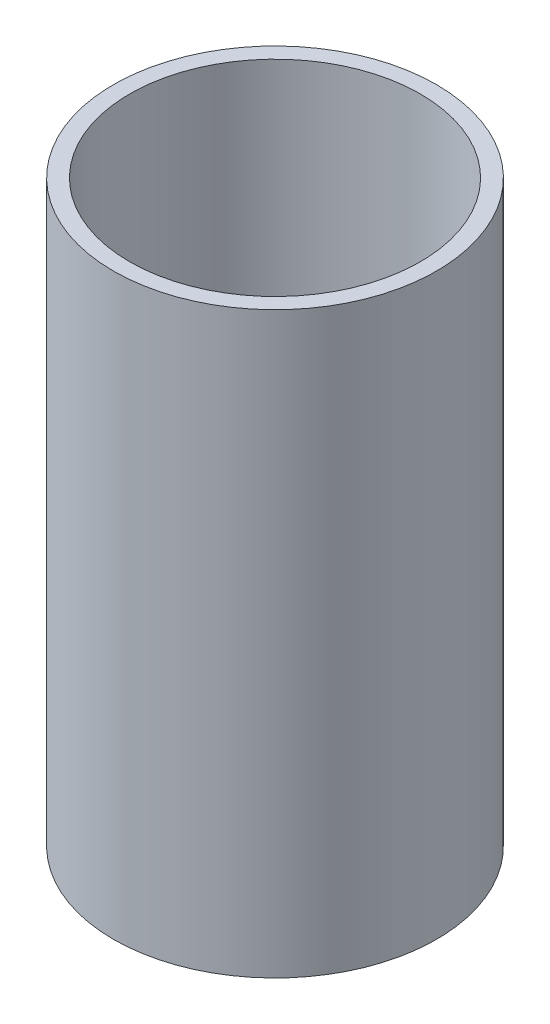
SolidWorks part; units mm, degrees
ref_plane "Front Plane" through (0, 0, 0) normal (0, 0, 1) x (1, 0, 0)
ref_plane "Top Plane" through (0, 0, 0) normal (0, 1, 0) x (1, 0, 0)
ref_plane "Right Plane" through (0, 0, 0) normal (1, 0, 0) x (0, 0, -1)
sketch "Sketch1" plane through (0, 0, 0) normal (0, 1, 0) x (1, 0, 0)
  circle A0 centre (0, 0) radius 20
  circle A1 centre (0, 0) radius 36
  circle A2 centre (0, 0) radius 40
  dimension "D1" = 40
  dimension "D2" = 72
  dimension "D3" = 80
extrude "Boss-Extrude1" add sketch "Sketch1" along normal blind 10
sketch "Sketch2" plane through (0, 0, 0) normal (0, 0, 1) x (1, 0, 0)
  line L0 (0, 85.4193) -> (0, -73.7814) construction
sketch "Sketch3" plane through (0, 0, 0) normal (1, 0, 0) x (0, 0, -1)
  line L0 (-40, 0) -> (40, 0) construction
  line L1 (-36, 10) -> (-20, 10) construction
  line L2 (-36, 10) -> (-36, 0) construction
  line L3 (-36, 0) -> (-20, 0) construction
  line L4 (-20, 10) -> (-20, 0) construction
  line L5 (20, 10) -> (-20, 10) construction
  line L6 (-20, 10) -> (-20, 0) construction
sketch "Sketch4" plane through (0, 0, 0) normal (1, 0, 0) x (0, 0, -1)
  line L0 (-4.2624, 0) -> (4.0314, 10)
  line L1 (-40, 0) -> (40, 0) construction
  line L2 (40, 10) -> (-40, 10) construction
  line L3 (-2.9787, 0) -> (5.3151, 10)
  line L4 (5.3151, 10) -> (4.0314, 10)
  line L5 (-4.2624, 0) -> (-2.9787, 0)
extrude "Boss-Extrude2" add sketch "Sketch4" against normal up to next and the other way up to next from offset 30
pattern_circular "CirPattern1" count 12 over 360 about axis through (0, 0, 0) along (0, 1, 0) of "Boss-Extrude2"
sketch "Sketch5" plane through (0, 10, 0) normal (0, 1, 0) x (1, 0, 0)
  line L0 (-18.685, 0) -> (17.5222, 0) construction
  line L1 (0, 15.5239) -> (0, -14.8175) construction
  circle A0 centre (-14.887, 0) radius 1.7357
  circle A1 centre (-7.4435, 12.8925) radius 1.7357
  circle A2 centre (7.4435, 12.8925) radius 1.7357
  circle A3 centre (14.887, 0) radius 1.7357
  circle A4 centre (7.4435, -12.8925) radius 1.7357
  circle A5 centre (-7.4435, -12.8925) radius 1.7357
  point P20 (0, 0)
  dimension "D1" = 6
extrude "Boss-Extrude3" add sketch "Sketch5" along normal blind 5
scale "Scale1" scale about origin uniform scaling yes scale factor 0.75
sketch "Sketch6" plane through (0, 7.5, 0) normal (0, 1, 0) x (1, 0, 0)
  circle A0 centre (0, 0) radius 30
  circle A1 centre (0, 0) radius 27
extrude "Boss-Extrude4" add sketch "Sketch6" along normal blind 100
equation "\"D1@Sketch1\"= \"D3@Sketch1\" / 2"
